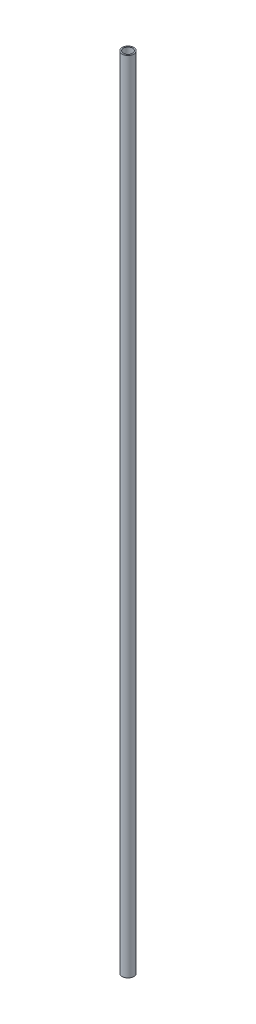
SolidWorks part; units mm, degrees
material "Hexcel AS4C (3000 Filaments)"
ref_plane "Front Plane" through (0, 0, 0) normal (0, 0, 1) x (1, 0, 0)
ref_plane "Top Plane" through (0, 0, 0) normal (0, 1, 0) x (1, 0, 0)
ref_plane "Right Plane" through (0, 0, 0) normal (1, 0, 0) x (0, 0, -1)
sketch "Sketch1" plane through (0, 0, 0) normal (0, 1, 0) x (1, 0, 0)
  circle A0 centre (0, 0) radius 4
  circle A1 centre (0, 0) radius 5.1
  dimension "D1" = 8
  dimension "D2" = 10.2
extrude "Boss-Extrude1" add sketch "Sketch1" along normal blind 703
